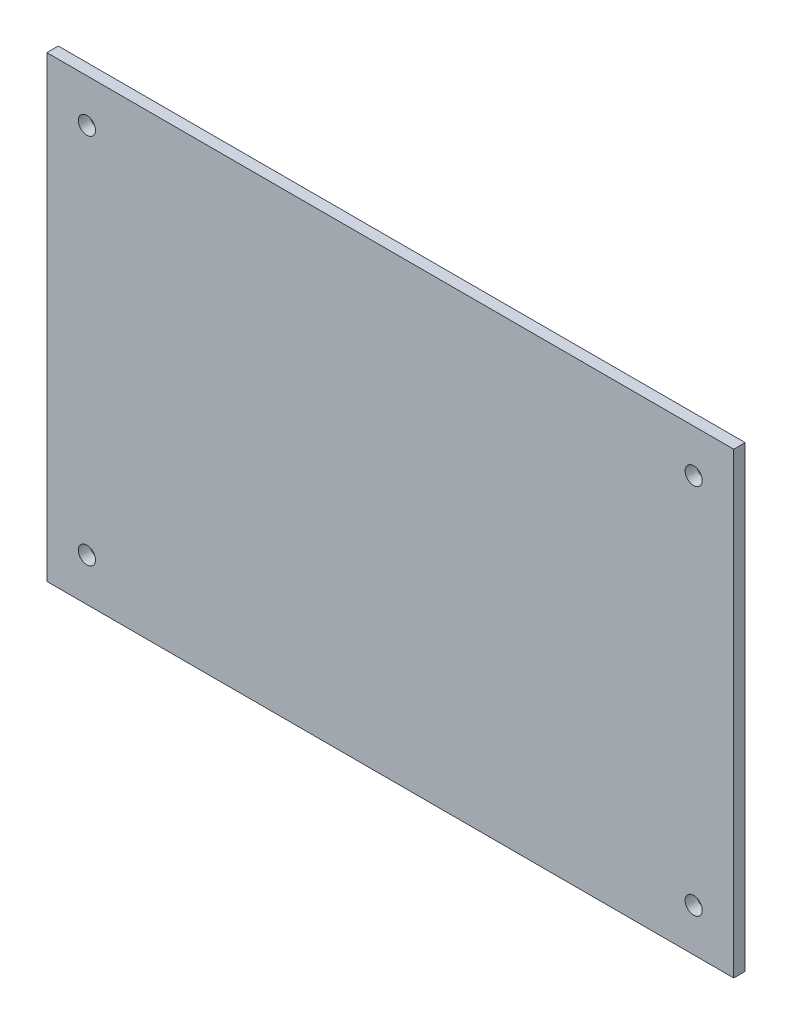
SolidWorks part; units mm, degrees
material "SMA"
ref_plane "Plan de face" through (0, 0, 0) normal (0, 0, 1) x (1, 0, 0)
ref_plane "Plan de dessus" through (0, 0, 0) normal (0, 1, 0) x (1, 0, 0)
ref_plane "Plan de droite" through (0, 0, 0) normal (1, 0, 0) x (0, 0, -1)
sketch "Esquisse1" plane through (0, 0, 0) normal (0, 0, 1) x (1, 0, 0)
  line L1 (60, -40) -> (-60, -40)
  line L2 (60, -40) -> (60, 40)
  line L3 (60, 40) -> (-60, 40)
  line L4 (-60, -40) -> (-60, 40)
  line L5 (60, -40) -> (-60, 40) construction
  line L6 (60, 40) -> (-60, -40) construction
  line L7 (53, -32.5) -> (-53, -32.5) construction
  line L8 (53, -32.5) -> (53, 32.5) construction
  line L9 (53, 32.5) -> (-53, 32.5) construction
  line L10 (-53, -32.5) -> (-53, 32.5) construction
  line L11 (53, -32.5) -> (-53, 32.5) construction
  line L12 (53, 32.5) -> (-53, -32.5) construction
  circle A0 centre (-53, 32.5) radius 1.5
  circle A1 centre (53, 32.5) radius 1.5
  circle A2 centre (53, -32.5) radius 1.5
  circle A3 centre (-53, -32.5) radius 1.5
  point P0 (0, 0)
  point P6 (0, 0)
  point P15 (-53, 19.5777)
  dimension "D4" = 3
  dimension "D1" = 120
  dimension "D2" = 80
  dimension "D3" = 106
  dimension "D5" = 65
extrude "Boss.-Extru.1" add sketch "Esquisse1" along normal blind 2
